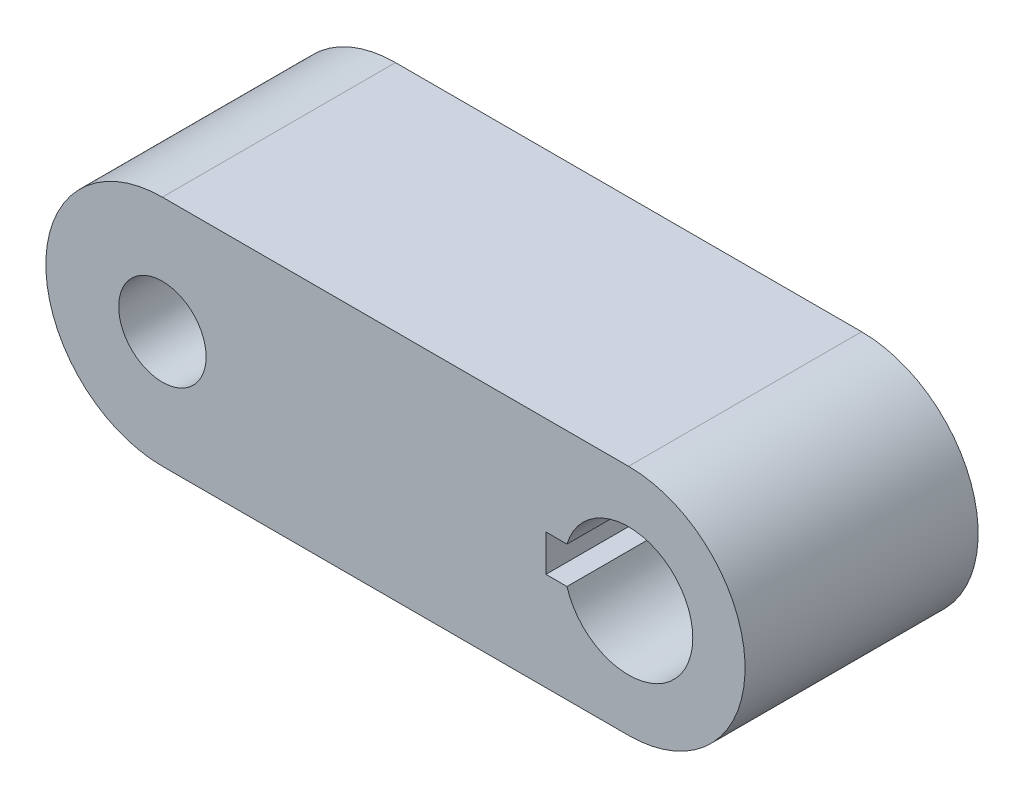
SolidWorks part; units mm, degrees
material "Plain Carbon Steel"
ref_plane "Front Plane" through (0, 0, 0) normal (0, 0, 1) x (1, 0, 0)
ref_plane "Top Plane" through (0, 0, 0) normal (0, 1, 0) x (1, 0, 0)
ref_plane "Right Plane" through (0, 0, 0) normal (1, 0, 0) x (0, 0, -1)
sketch "Sketch1" plane through (0, 0, 0) normal (0, 0, 1) x (1, 0, 0)
  line L0 (0, 0) -> (25.4, 0) construction
  line L1 (0, 6.35) -> (25.4, 6.35)
  line L2 (0, -6.35) -> (25.4, -6.35)
  arc A0 (0, 6.35) -> (0, -6.35) centre (0, 0) ccw
  arc A1 (25.4, -6.35) -> (25.4, 6.35) centre (25.4, 0) ccw
  point P3 (12.7, 0)
  dimension "D1" = 25.4
  dimension "D2" = 12.7
extrude "Main Body" add sketch "Sketch1" along normal mid plane 12.7
hole_wizard "3/16 (0.1875) Diameter Hole1" positions "Sketch3" profile "Sketch2" hole size "3/16" standard "Ansi Inch" end condition through all
sketch "Sketch3" plane through (0, 0, 6.35) normal (0, 0, 1) x (1, 0, 0)
  arc A0 (0, 6.35) -> (0, -6.35) centre (0, 0) ccw construction
  point P0 (0, 0)
sketch "Sketch2" plane through (0, 0, 6.35) normal (1, 0, 0) x (0, -1, 0)
  line L0 (0, 0) -> (0, 12.7)
  line L1 (0, 12.7) -> (2.3812, 12.7)
  line L2 (2.3812, 12.7) -> (2.3812, 0)
  line L5 (2.3812, 0) -> (0, 0)
  line L11 (0, -6.35) -> (0, 107.95) construction
  dimension "Thru Hole Dia." = 4.7625
  dimension "Thru Hole Depth" = 12.7
hole_wizard "Ø7.0 (7) Diameter Hole1" positions "Sketch5" profile "Sketch4" hole size "Ø7.0" standard "ANSI Metric"
sketch "Sketch5" plane through (0, 0, 6.35) normal (0, 0, 1) x (1, 0, 0)
  arc A0 (25.4, -6.35) -> (25.4, 6.35) centre (25.4, 0) ccw construction
  point P0 (25.4, 0)
sketch "Sketch4" plane through (25.4, 0, 6.35) normal (1, 0, 0) x (0, -1, 0)
  line L0 (0, 0) -> (0, 14.803)
  line L1 (0, 14.803) -> (3.5, 12.7)
  line L2 (3.5, 12.7) -> (3.5, 0)
  line L5 (3.5, 0) -> (0, 0)
  line L10 (0, 14.803) -> (-3.5, 12.7) construction
  line L11 (0, -6.35) -> (0, 107.95) construction
  dimension "Hole Dia." = 7
  dimension "Hole Depth" = 12.7
  dimension "Drill Angle" = 118
sketch "Sketch6" plane through (0, 0, 6.35) normal (0, 0, 1) x (1, 0, 0)
  line L0 (25.4, 0) -> (18.145, 0) construction
  line L2 (23.4, -1) -> (20.9, -1)
  line L3 (23.4, -1) -> (23.4, 1)
  line L4 (23.4, 1) -> (20.9, 1)
  line L5 (20.9, -1) -> (20.9, 1)
  circle A0 centre (25.4, 0) radius 3.5 construction
  point P10 (20.9, 0)
  dimension "D1" = 2
  dimension "D2" = 4.5
  dimension "D3" = 2.5
extrude "Cut-2x2 Keyway" cut sketch "Sketch6" against normal through all
